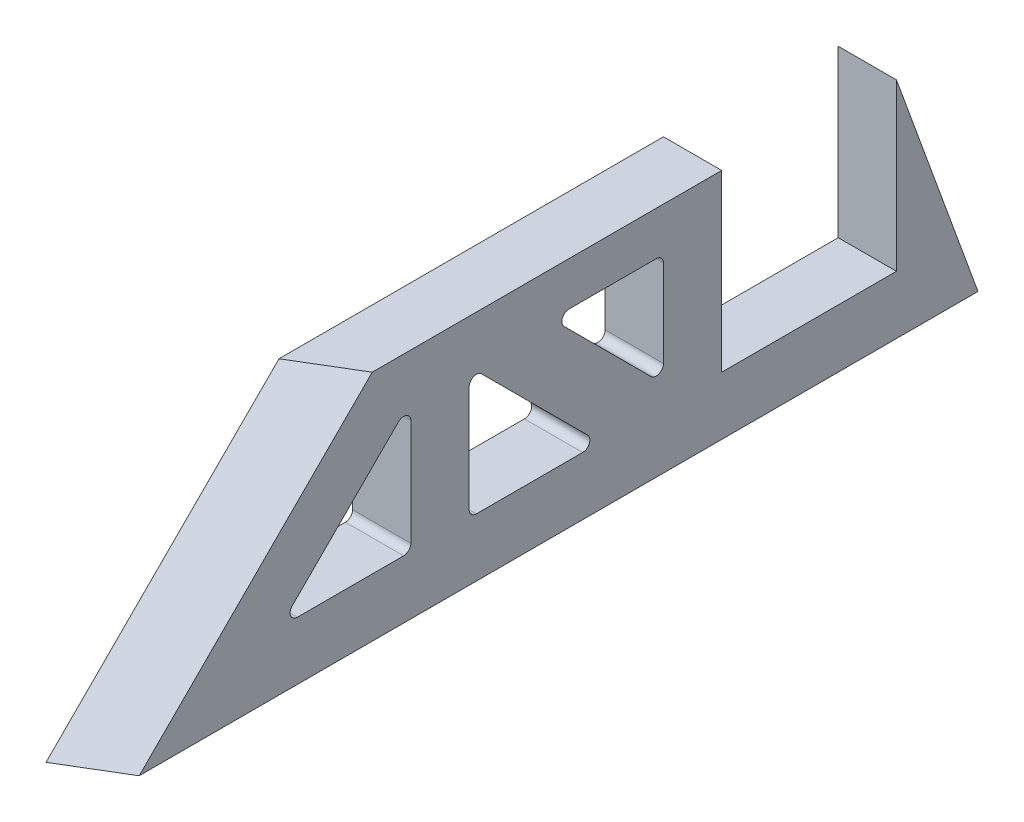
SolidWorks part; units mm, degrees
material "PE High Density"
ref_plane "Front Plane" through (0, 0, 0) normal (0, 0, 1) x (1, 0, 0)
ref_plane "Top Plane" through (0, 0, 0) normal (0, 1, 0) x (1, 0, 0)
ref_plane "Right Plane" through (0, 0, 0) normal (1, 0, 0) x (0, 0, -1)
sketch "Sketch1" plane through (0, 0, 0) normal (1, 0, 0) x (0, 0, -1)
  line L0 (-95.25, 0) -> (95.25, 0)
  line L1 (95.25, 0) -> (77.47, 48.8501)
  line L2 (77.47, 48.8501) -> (77.47, 12.7)
  line L3 (77.47, 12.7) -> (39.37, 12.7)
  line L4 (39.37, 12.7) -> (39.37, 50.8)
  line L5 (39.37, 50.8) -> (-44.45, 50.8)
  line L6 (-44.45, 50.8) -> (-95.25, 0)
  point P4 (0, 0)
  dimension "D1" = 45
  dimension "D2" = 12.7
  dimension "D3" = 38.1
  dimension "D4" = 50.8
  dimension "D5" = 70
  dimension "D6" = 17.78
  dimension "D7" = 190.5
extrude "Boss-Extrude1" add sketch "Sketch1" along normal blind 12.7
sketch "Sketch2" plane through (0, 0, 0) normal (0, -1, 0) x (-1, 0, 0)
  line L0 (0, -95.25) -> (-12.7, -95.25)
  line L1 (-12.7, -95.25) -> (-12.7, -87.63)
  line L2 (-12.7, -95.25) -> (-12.7, 95.25) construction
  line L3 (-12.7, -87.63) -> (0, -95.25)
  dimension "D1" = 7.62
extrude "Cut-Extrude1" cut sketch "Sketch2" along direction (0, -0.7071, 0.7071) on the side against the normal through all
sketch "Sketch4" plane through (12.7, 0, 0) normal (1, 0, 0) x (0, 0, -1)
  line L0 (-56.9695, 12.7) -> (-28.3945, 41.275)
  line L1 (-28.3945, 41.275) -> (-28.3945, 12.7)
  line L2 (-28.3945, 12.7) -> (-56.9695, 12.7)
  line L3 (-15.6945, 12.7) -> (-15.6945, 41.275)
  line L4 (-15.6945, 41.275) -> (12.8805, 12.7)
  line L5 (12.8805, 12.7) -> (-15.6945, 12.7)
  line L6 (2.266, 41.275) -> (26.67, 16.871)
  line L7 (26.67, 16.871) -> (26.67, 41.275)
  line L8 (26.67, 41.275) -> (2.266, 41.275)
  line L9 (-36.83, 50.8) -> (-87.63, 0) construction
  line L10 (-87.63, 0) -> (95.25, 0) construction
  line L11 (39.37, 50.8) -> (-36.83, 50.8) construction
  line L12 (39.37, 12.7) -> (39.37, 50.8) construction
  point P13 (0, 0)
  point P16 (0, 0)
  dimension "D1" = 12.7
  dimension "D2" = 12.7
  dimension "D3" = 9.525
  dimension "D4" = 12.7
  dimension "D5" = 12.7
  dimension "D6" = 12.7
extrude "Cut-Extrude2" cut sketch "Sketch4" against normal up to next
fillet "Fillet1" radius 1.5875 9 edges at (6.35, 12.7, 15.6945) (6.35, 12.7, 56.9695) (6.35, 16.871, -26.67) (6.35, 12.7, 28.3945) (6.35, 12.7, -12.8805) (6.35, 41.275, -2.266) (6.35, 41.275, -26.67) (6.35, 41.275, 28.3945) (6.35, 41.275, 15.6945)
